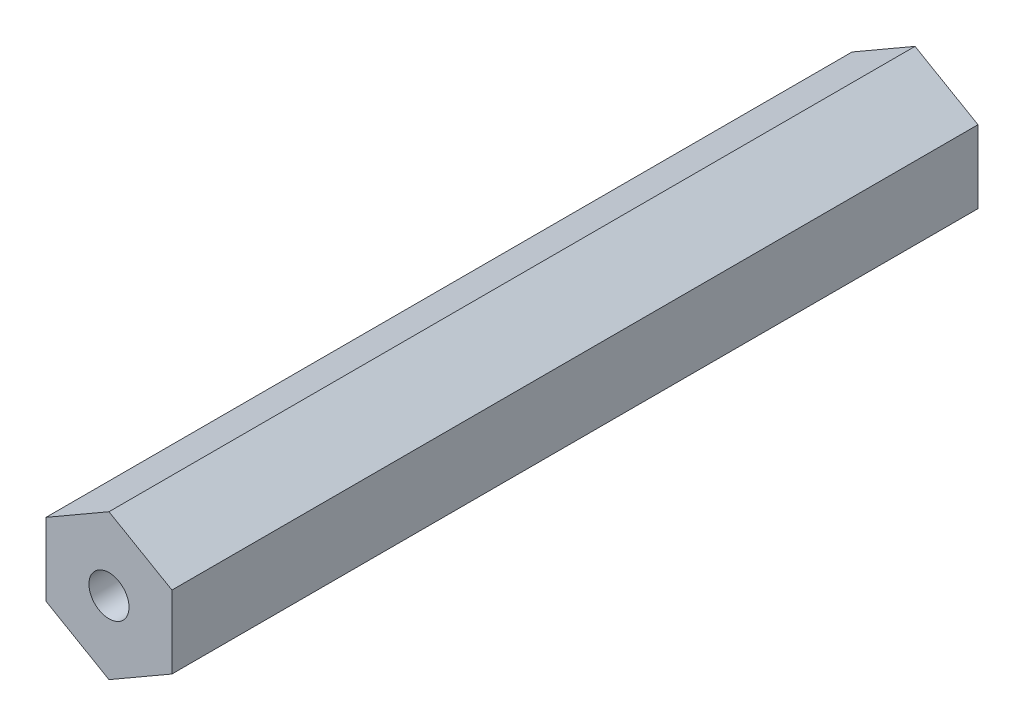
SolidWorks part; units mm, degrees
other "Markup1"
sketch "Sketch3" plane through (6.35, 7.3323, -19.05) normal (0.3384, 0.0641, -0.9388) x (-0.9259, -0.1556, -0.3443)
ref_plane "Front Plane" through (0, 0, 0) normal (0, 0, 1) x (1, 0, 0)
ref_plane "Top Plane" through (0, 0, 0) normal (0, 1, 0) x (1, 0, 0)
ref_plane "Right Plane" through (0, 0, 0) normal (1, 0, 0) x (0, 0, -1)
sketch "Sketch1" plane through (0, 0, 0) normal (0, 0, 1) x (1, 0, 0)
  line L1 (0, 7.3323) -> (-6.35, 3.6662)
  line L2 (-6.35, 3.6662) -> (-6.35, -3.6662)
  line L3 (-6.35, -3.6662) -> (0, -7.3323)
  line L4 (0, -7.3323) -> (6.35, -3.6662)
  line L5 (6.35, -3.6662) -> (6.35, 3.6662)
  line L6 (6.35, 3.6662) -> (0, 7.3323)
  circle A0 centre (0, 0) radius 6.35 construction
  dimension "D1" = 12.7
extrude "Boss-Extrude1" add sketch "Sketch1" along normal mid plane 81.28
sketch "Sketch2" plane through (0, 0, -40.64) normal (0, 0, -1) x (-1, 0, 0)
  circle A0 centre (0, 0) radius 2.0193
  dimension "D1" = 4.0386
extrude "Cut-Extrude1" cut sketch "Sketch2" against normal through all
